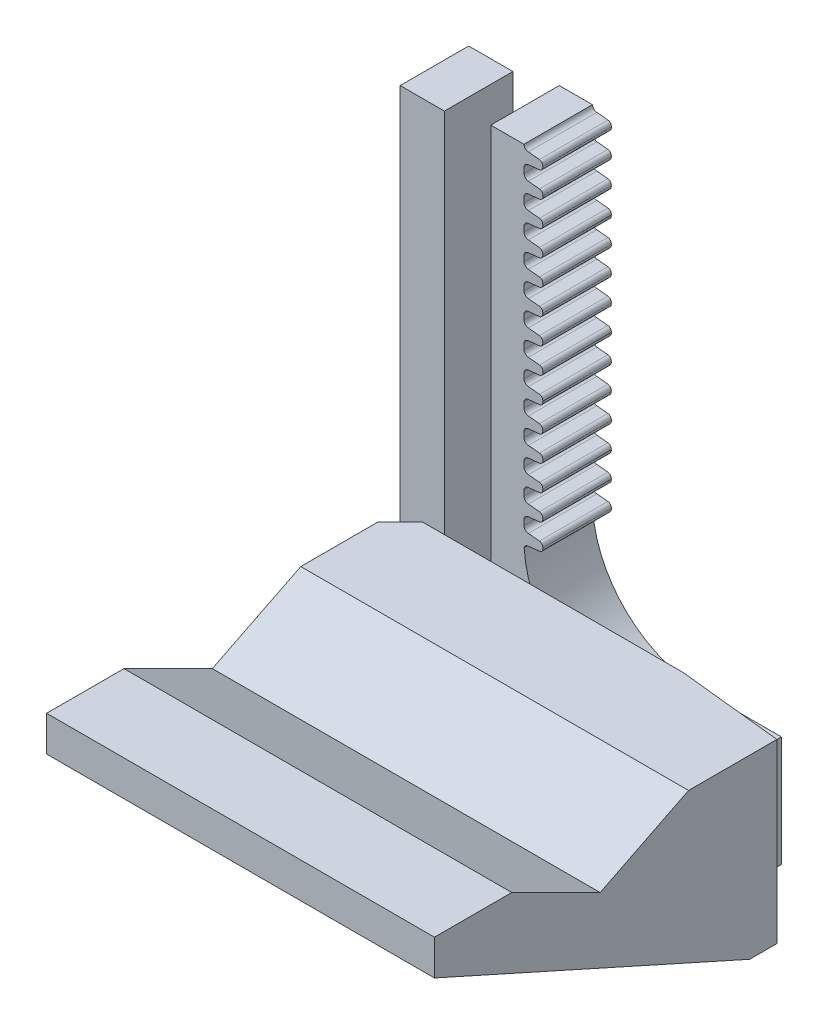
SolidWorks part; units mm, degrees
ref_plane "Front Plane" through (0, 0, 0) normal (0, 0, 1) x (1, 0, 0)
ref_plane "Top Plane" through (0, 0, 0) normal (0, 1, 0) x (1, 0, 0)
ref_plane "Right Plane" through (0, 0, 0) normal (1, 0, 0) x (0, 0, -1)
sketch "Sketch1" plane through (0, 0, 0) normal (0, 0, 1) x (1, 0, 0)
  line L1 (-28.3, 0) -> (0, 0)
  line L6 (-17.1, 20) -> (-17.1, 51)
  line L7 (-17.1, 51) -> (-20.1, 51)
  line L9 (0, 10) -> (-7.1, 10)
  line L11 (-20.1, 51) -> (-20.1, 6)
  line L12 (-28.3, 0) -> (-28.3, 50)
  line L13 (-28.3, 50) -> (-24.3, 50)
  line L14 (-24.3, 50) -> (-24.3, 6)
  line L15 (-24.3, 6) -> (-20.1, 6)
  line L16 (0, 10) -> (0, 0)
  arc A1 (-17.1, 20) -> (-7.1, 10) centre (-7.1, 20) ccw
  dimension "D8" = 10
  dimension "D1" = 45
  dimension "D2" = 4.2
  dimension "D3" = 3
  dimension "D4" = 17.1
  dimension "D5" = 50
  dimension "D6" = 6
  dimension "D7" = 10
  dimension "D9" = 4
extrude "Boss-Extrude1" add sketch "Sketch1" along normal blind 6.2
sketch "Sketch2" plane through (0, 0, 0) normal (0, -1, 0) x (1, 0, 0)
  line L0 (0, 6.2) -> (0, 10.4)
  line L1 (0, 10.4) -> (11, 10.4)
  line L2 (11, 10.4) -> (11, 42.4)
  line L3 (11, 42.4) -> (-24.1, 42.4)
  line L4 (-24.1, 42.4) -> (-24.1, 10.4)
  line L5 (-24.1, 10.4) -> (-13.1, 10.4)
  line L6 (-13.1, 10.4) -> (-13.1, 6.2)
  line L7 (-28.3, 6.2) -> (0, 6.2) construction
  line L8 (-13.1, 6.2) -> (0, 6.2)
  dimension "D1" = 4.2
  dimension "D2" = 7
  dimension "D3" = 11
  dimension "D4" = 11
  dimension "D5" = 32
extrude "Boss-Extrude2" add sketch "Sketch2" against normal blind 21
chamfer "Chamfer1" distance 5 angle 80 1 edges at (-6.55, 0, 42.4)
sketch "Sketch3" plane through (0, 0, 0) normal (1, 0, 0) x (0, 0, -1)
  line L0 (-6.2, 10) -> (-7.6, 10)
  line L1 (-7.6, 10) -> (-10.4, 21)
  line L2 (-10.4, 21) -> (-6.2, 21)
  line L3 (-6.2, 21) -> (-6.2, 10)
  dimension "D1" = 1.4
extrude "Cut-Extrude1" cut sketch "Sketch3" against normal up to next
chamfer "Chamfer2" distance 1 angle 84 1 edges at (11, 10.5, 10.4)
chamfer "Chamfer3" distance 2 angle 45 1 edges at (-24.1, 10.5, 10.4)
sketch "Sketch5" plane through (11, 0, 0) normal (1, 0, 0) x (0, 0, -1)
  line L0 (-42.4, 17.8) -> (-13.8689, 5)
  line L1 (-42.4, 21) -> (-42.4, 5) construction
  line L3 (-13.8689, 5) -> (-10.9662, -4.1087)
  line L4 (-10.9662, -4.1087) -> (-44.0369, 0.9377)
  line L5 (-44.0369, 0.9377) -> (-42.4, 17.8)
  line L6 (-11.4, 21) -> (-10.4, 21) construction
  dimension "D1" = 3.2
  dimension "D2" = 16
extrude "Cut-Extrude2" cut sketch "Sketch5" against normal up to next
sketch "Sketch6" plane through (0, 0, 10.4) normal (0, 0, -1) x (-1, 0, 0)
  line L0 (13.1, 0) -> (24.1, 5)
  line L1 (24.1, 5) -> (37.1983, 5)
  line L3 (-20.705, 5) -> (-11, 5)
  line L4 (-11, 5) -> (0, 0)
  line L5 (0, 0) -> (13.1, 0)
  line L6 (37.1983, 5) -> (28.626, -4.5222)
  line L7 (28.626, -4.5222) -> (-13.826, -5.6293)
  line L8 (-13.826, -5.6293) -> (-20.705, 5)
extrude "Cut-Extrude3" cut sketch "Sketch6" against normal up to next
sketch "Sketch7" plane through (0, 0, 6.2) normal (0, 0, 1) x (1, 0, 0)
  line L0 (-17.1, 20) -> (-17.1, 51) construction
  line L1 (-15.4, 50.1) -> (-17.4129, 50.1) construction
  line L2 (-16.7, 50.6) -> (-15.7, 50.5)
  line L3 (-16.7, 49.6) -> (-15.7, 49.7)
  line L4 (-17.1, 49.2) -> (-17.1, 48.7)
  line L5 (-16.7, 48.3) -> (-15.7, 48.2)
  line L6 (-16.7, 47.3) -> (-15.7, 47.4)
  line L7 (-17.1, 46.9) -> (-17.1, 46.4)
  line L8 (-16.7, 46) -> (-15.7, 45.9)
  line L9 (-16.7, 45) -> (-15.7, 45.1)
  line L10 (-17.1, 44.6) -> (-17.1, 44.1)
  line L11 (-16.7, 43.7) -> (-15.7, 43.6)
  line L12 (-16.7, 42.7) -> (-15.7, 42.8)
  line L13 (-17.1, 42.3) -> (-17.1, 41.8)
  line L14 (-16.7, 41.4) -> (-15.7, 41.3)
  line L15 (-16.7, 40.4) -> (-15.7, 40.5)
  line L16 (-17.1, 40) -> (-17.1, 39.5)
  line L17 (-16.7, 39.1) -> (-15.7, 39)
  line L18 (-16.7, 38.1) -> (-15.7, 38.2)
  line L19 (-17.1, 37.7) -> (-17.1, 37.2)
  line L20 (-16.7, 36.8) -> (-15.7, 36.7)
  line L21 (-16.7, 35.8) -> (-15.7, 35.9)
  line L22 (-17.1, 35.4) -> (-17.1, 34.9)
  line L23 (-16.7, 34.5) -> (-15.7, 34.4)
  line L24 (-16.7, 33.5) -> (-15.7, 33.6)
  line L25 (-17.1, 33.1) -> (-17.1, 32.6)
  line L26 (-16.7, 32.2) -> (-15.7, 32.1)
  line L27 (-16.7, 31.2) -> (-15.7, 31.3)
  line L28 (-17.1, 30.8) -> (-17.1, 30.3)
  line L29 (-16.7, 29.9) -> (-15.7, 29.8)
  line L30 (-16.7, 28.9) -> (-15.7, 29)
  line L31 (-17.1, 28.5) -> (-17.1, 28)
  line L32 (-16.7, 27.6) -> (-15.7, 27.5)
  line L33 (-16.7, 26.6) -> (-15.7, 26.7)
  line L34 (-17.1, 26.2) -> (-17.1, 25.7)
  line L35 (-16.7, 25.3) -> (-15.7, 25.2)
  line L36 (-16.7, 24.3) -> (-15.7, 24.4)
  line L37 (-17.1, 23.9) -> (-17.1, 23.4)
  line L38 (-16.7, 23) -> (-15.7, 22.9)
  line L39 (-16.7, 22) -> (-15.7, 22.1)
  line L40 (-17.1, 21.6) -> (-17.1, 21.1)
  line L41 (-16.7, 20.7) -> (-15.7, 20.6)
  line L42 (-16.7, 19.7) -> (-15.7, 19.8)
  line L43 (-17.1, 19.3) -> (-17.1, 18.8)
  line L44 (-17.1, 18.8) -> (-18.685, 49.2)
  line L45 (-18.685, 49.2) -> (-17.1, 51)
  arc A0 (-17.1, 51) -> (-16.7, 50.6) centre (-16.6556, 51.0444) ccw
  arc A1 (-15.7, 50.5) -> (-15.4, 50.1) centre (-15.7338, 50.1622) cw
  arc A2 (-17.1, 49.2) -> (-16.7, 49.6) centre (-16.6556, 49.1556) cw
  arc A3 (-15.7, 49.7) -> (-15.4, 50.1) centre (-15.7338, 50.0378) ccw
  arc A4 (-17.1, 48.7) -> (-16.7, 48.3) centre (-16.6556, 48.7444) ccw
  arc A5 (-15.7, 48.2) -> (-15.4, 47.8) centre (-15.7338, 47.8622) cw
  arc A6 (-17.1, 46.9) -> (-16.7, 47.3) centre (-16.6556, 46.8556) cw
  arc A7 (-15.7, 47.4) -> (-15.4, 47.8) centre (-15.7338, 47.7378) ccw
  arc A8 (-17.1, 46.4) -> (-16.7, 46) centre (-16.6556, 46.4444) ccw
  arc A9 (-15.7, 45.9) -> (-15.4, 45.5) centre (-15.7338, 45.5622) cw
  arc A10 (-17.1, 44.6) -> (-16.7, 45) centre (-16.6556, 44.5556) cw
  arc A11 (-15.7, 45.1) -> (-15.4, 45.5) centre (-15.7338, 45.4378) ccw
  arc A12 (-17.1, 44.1) -> (-16.7, 43.7) centre (-16.6556, 44.1444) ccw
  arc A13 (-15.7, 43.6) -> (-15.4, 43.2) centre (-15.7338, 43.2622) cw
  arc A14 (-17.1, 42.3) -> (-16.7, 42.7) centre (-16.6556, 42.2556) cw
  arc A15 (-15.7, 42.8) -> (-15.4, 43.2) centre (-15.7338, 43.1378) ccw
  arc A16 (-17.1, 41.8) -> (-16.7, 41.4) centre (-16.6556, 41.8444) ccw
  arc A17 (-15.7, 41.3) -> (-15.4, 40.9) centre (-15.7338, 40.9622) cw
  arc A18 (-17.1, 40) -> (-16.7, 40.4) centre (-16.6556, 39.9556) cw
  arc A19 (-15.7, 40.5) -> (-15.4, 40.9) centre (-15.7338, 40.8378) ccw
  arc A20 (-17.1, 39.5) -> (-16.7, 39.1) centre (-16.6556, 39.5444) ccw
  arc A21 (-15.7, 39) -> (-15.4, 38.6) centre (-15.7338, 38.6622) cw
  arc A22 (-17.1, 37.7) -> (-16.7, 38.1) centre (-16.6556, 37.6556) cw
  arc A23 (-15.7, 38.2) -> (-15.4, 38.6) centre (-15.7338, 38.5378) ccw
  arc A24 (-17.1, 37.2) -> (-16.7, 36.8) centre (-16.6556, 37.2444) ccw
  arc A25 (-15.7, 36.7) -> (-15.4, 36.3) centre (-15.7338, 36.3622) cw
  arc A26 (-17.1, 35.4) -> (-16.7, 35.8) centre (-16.6556, 35.3556) cw
  arc A27 (-15.7, 35.9) -> (-15.4, 36.3) centre (-15.7338, 36.2378) ccw
  arc A28 (-17.1, 34.9) -> (-16.7, 34.5) centre (-16.6556, 34.9444) ccw
  arc A29 (-15.7, 34.4) -> (-15.4, 34) centre (-15.7338, 34.0622) cw
  arc A30 (-17.1, 33.1) -> (-16.7, 33.5) centre (-16.6556, 33.0556) cw
  arc A31 (-15.7, 33.6) -> (-15.4, 34) centre (-15.7338, 33.9378) ccw
  arc A32 (-17.1, 32.6) -> (-16.7, 32.2) centre (-16.6556, 32.6444) ccw
  arc A33 (-15.7, 32.1) -> (-15.4, 31.7) centre (-15.7338, 31.7622) cw
  arc A34 (-17.1, 30.8) -> (-16.7, 31.2) centre (-16.6556, 30.7556) cw
  arc A35 (-15.7, 31.3) -> (-15.4, 31.7) centre (-15.7338, 31.6378) ccw
  arc A36 (-17.1, 30.3) -> (-16.7, 29.9) centre (-16.6556, 30.3444) ccw
  arc A37 (-15.7, 29.8) -> (-15.4, 29.4) centre (-15.7338, 29.4622) cw
  arc A38 (-17.1, 28.5) -> (-16.7, 28.9) centre (-16.6556, 28.4556) cw
  arc A39 (-15.7, 29) -> (-15.4, 29.4) centre (-15.7338, 29.3378) ccw
  arc A40 (-17.1, 28) -> (-16.7, 27.6) centre (-16.6556, 28.0444) ccw
  arc A41 (-15.7, 27.5) -> (-15.4, 27.1) centre (-15.7338, 27.1622) cw
  arc A42 (-17.1, 26.2) -> (-16.7, 26.6) centre (-16.6556, 26.1556) cw
  arc A43 (-15.7, 26.7) -> (-15.4, 27.1) centre (-15.7338, 27.0378) ccw
  arc A44 (-17.1, 25.7) -> (-16.7, 25.3) centre (-16.6556, 25.7444) ccw
  arc A45 (-15.7, 25.2) -> (-15.4, 24.8) centre (-15.7338, 24.8622) cw
  arc A46 (-17.1, 23.9) -> (-16.7, 24.3) centre (-16.6556, 23.8556) cw
  arc A47 (-15.7, 24.4) -> (-15.4, 24.8) centre (-15.7338, 24.7378) ccw
  arc A48 (-17.1, 23.4) -> (-16.7, 23) centre (-16.6556, 23.4444) ccw
  arc A49 (-15.7, 22.9) -> (-15.4, 22.5) centre (-15.7338, 22.5622) cw
  arc A50 (-17.1, 21.6) -> (-16.7, 22) centre (-16.6556, 21.5556) cw
  arc A51 (-15.7, 22.1) -> (-15.4, 22.5) centre (-15.7338, 22.4378) ccw
  arc A52 (-17.1, 21.1) -> (-16.7, 20.7) centre (-16.6556, 21.1444) ccw
  arc A53 (-15.7, 20.6) -> (-15.4, 20.2) centre (-15.7338, 20.2622) cw
  arc A54 (-17.1, 19.3) -> (-16.7, 19.7) centre (-16.6556, 19.2556) cw
  arc A55 (-15.7, 19.8) -> (-15.4, 20.2) centre (-15.7338, 20.1378) ccw
  dimension "D1" = 0.4
  dimension "D6" = 0.4
  dimension "D2" = 0.3
  dimension "D3" = 0.4
  dimension "D4" = 0.1
  dimension "D5" = 1
  dimension "D7" = 14
extrude "Boss-Extrude3" add sketch "Sketch7" against normal up to surface (6.2 mm away) up to face at (-17.161, 22.9026, 0)
sketch "Sketch8" plane through (11, 0, 0) normal (1, 0, 0) x (0, 0, -1)
  line L0 (-35.4, 21) -> (-27.4, 17)
  line L1 (-11.4, 21) -> (-42.4, 21) construction
  line L2 (-27.4, 17) -> (-19.4, 21)
  line L3 (-19.4, 21) -> (-35.4, 21)
  dimension "D1" = 4
  dimension "D2" = 16
  dimension "D3" = 7
  dimension "D4" = 8
extrude "Cut-Extrude4" cut sketch "Sketch8" against normal up to next
equation "\"D4@Sketch8\"=\"D2@Sketch8\"/2"
